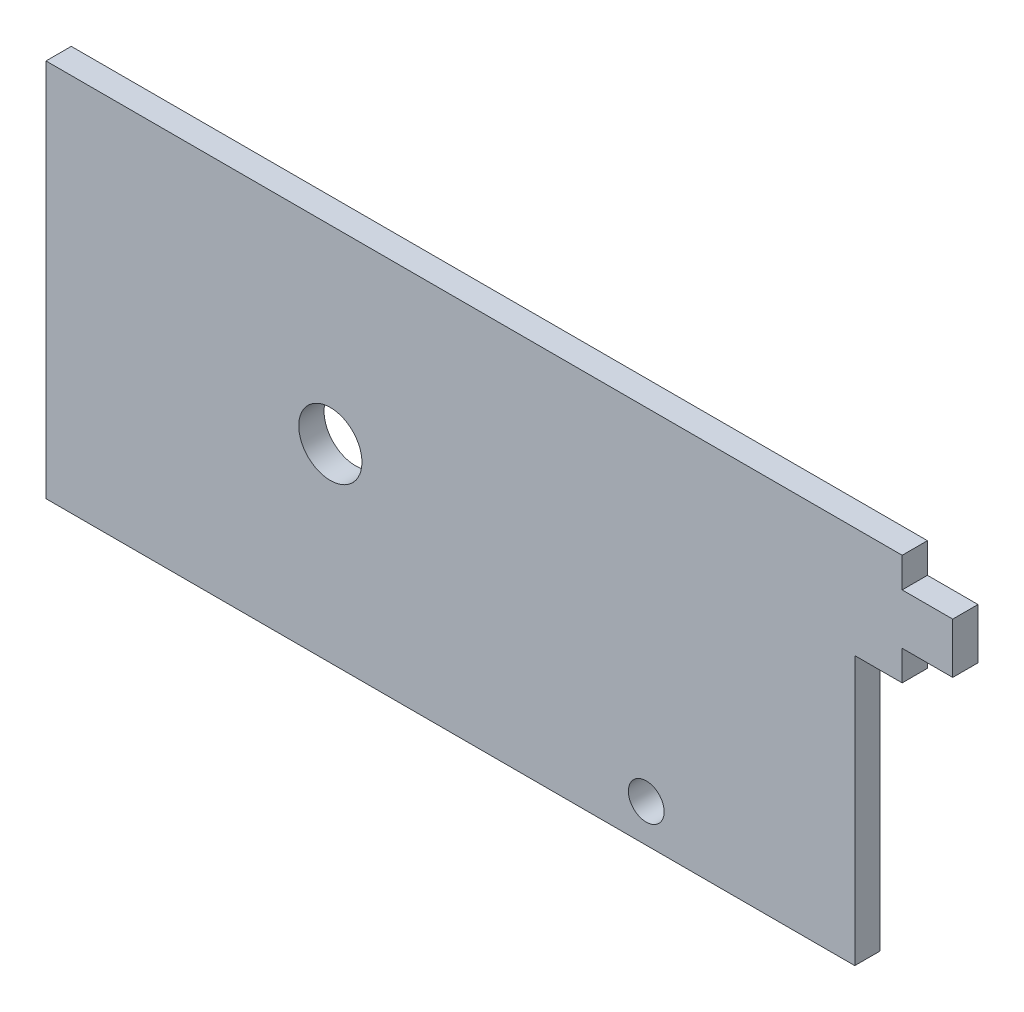
SolidWorks part; units mm, degrees
ref_plane "Front Plane" through (0, 0, 0) normal (0, 0, 1) x (1, 0, 0)
ref_plane "Top Plane" through (0, 0, 0) normal (0, 1, 0) x (1, 0, 0)
ref_plane "Right Plane" through (0, 0, 0) normal (1, 0, 0) x (0, 0, -1)
sketch "Sketch1" plane through (0, 0, 0) normal (0, 0, 1) x (1, 0, 0)
  line L0 (47, 30) -> (54.5, 30)
  line L1 (-81, -30) -> (47, -30)
  line L2 (-81, -30) -> (-81, 30)
  line L3 (-81, 30) -> (47, 30)
  line L4 (47, -30) -> (47, 30) construction
  line L6 (54.5, 12.5) -> (47, 12.5)
  line L11 (54.5, 30) -> (54.5, 12.5) construction
  line L12 (54.5, 30) -> (54.5, 25.25)
  line L13 (47, 12.5) -> (47, -30)
  line L14 (54.5, 25.25) -> (62.5, 25.25)
  line L15 (62.5, 25.25) -> (62.5, 17.25)
  line L16 (62.5, 17.25) -> (54.5, 17.25)
  line L17 (54.5, 17.25) -> (54.5, 12.5)
  circle A4 centre (-36, 0) radius 5
  circle A5 centre (14, -24) radius 2.83
  point P12 (-81, 0)
  dimension "D3" = 17.5
  dimension "D4" = 7.5
  dimension "D5" = 10
  dimension "D1" = 128
  dimension "D6" = 45
  dimension "D9" = 5.66
  dimension "D10" = 95
  dimension "D11" = 6
  dimension "D2" = 60
  dimension "D7" = 8
  dimension "D8" = 8
extrude "Boss-Extrude1" add sketch "Sketch1" along normal blind 4
